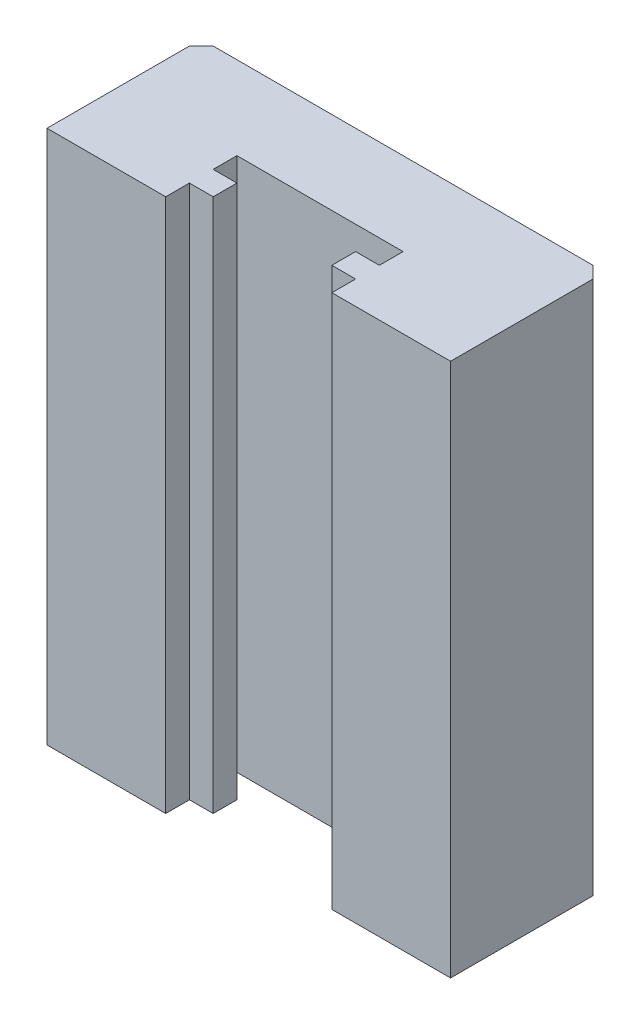
SolidWorks part; units mm, degrees
material "AISI 304"
ref_plane "前视基准面" through (0, 0, 0) normal (0, 0, 1) x (1, 0, 0)
ref_plane "上视基准面" through (0, 0, 0) normal (0, 1, 0) x (1, 0, 0)
ref_plane "右视基准面" through (0, 0, 0) normal (1, 0, 0) x (0, 0, -1)
other "Configuration Table"
sketch "草图1" plane through (0, 0, 0) normal (0, 1, 0) x (1, 0, 0)
  line L0 (0, 0) -> (0, -4.4812) construction
  line L1 (-8.5, -3.25) -> (8.5, -3.25)
  line L2 (-8.5, -3.25) -> (-8.5, 3.25)
  line L3 (-8.5, 3.25) -> (8.5, 3.25)
  line L4 (8.5, -3.25) -> (8.5, 3.25)
  line L5 (-8.5, -3.25) -> (8.5, 3.25) construction
  line L6 (-8.5, 3.25) -> (8.5, -3.25) construction
  line L7 (3.5, -3.25) -> (3.5, -2.25)
  line L8 (3.5, -2.25) -> (2.5, -2.25)
  line L9 (2.5, -2.25) -> (2.5, -1.25)
  line L10 (2.5, -1.25) -> (3.5, -1.25)
  line L11 (3.5, -1.25) -> (3.5, -0.25)
  line L12 (3.5, -0.25) -> (-3.5, -0.25)
  line L13 (-3.5, -1.25) -> (-3.5, -0.25)
  line L14 (-2.5, -1.25) -> (-3.5, -1.25)
  line L15 (-2.5, -2.25) -> (-2.5, -1.25)
  line L16 (-3.5, -2.25) -> (-2.5, -2.25)
  line L17 (-3.5, -3.25) -> (-3.5, -2.25)
  point P0 (0, 0)
  point P16 (0, -0.25)
  dimension "D1" = 6.5
  dimension "D2" = 17
  dimension "D3" = 3.5
  dimension "D4" = 3.5
  dimension "D5" = 1
  dimension "D6" = 1
  dimension "D7" = 1
  dimension "D8" = 1
extrude "凸台-拉伸1" add sketch "草图1" along normal blind 22.5 contours L1 L17 L16 L15 L14 L13 L12 L11 L10 L9 L8 L7 L4 L3 L2
sketch "草图2" plane through (0, 0, -3.25) normal (0, 0, -1) x (-1, 0, 0)
  line L0 (-8.5, 11.25) -> (15.5023, 11.25) construction
  line L1 (-8.5, 22.5) -> (-8.5, 0) construction
  line L2 (0, 0) -> (0, 23.093) construction
  circle A0 centre (6, 15.25) radius 1
  circle A1 centre (6, 7.25) radius 1
  circle A2 centre (-6, 7.25) radius 1
  circle A3 centre (-6, 15.25) radius 1
  dimension "D1" = 2
  dimension "D2" = 8
  dimension "D3" = 12
extrude "切除-拉伸1" cut sketch "草图2" against normal blind 4
chamfer "倒角1" distance 0.5 angle 45 2 edges at (8.5, 11.25, -3.25) (-8.5, 11.25, -3.25)
